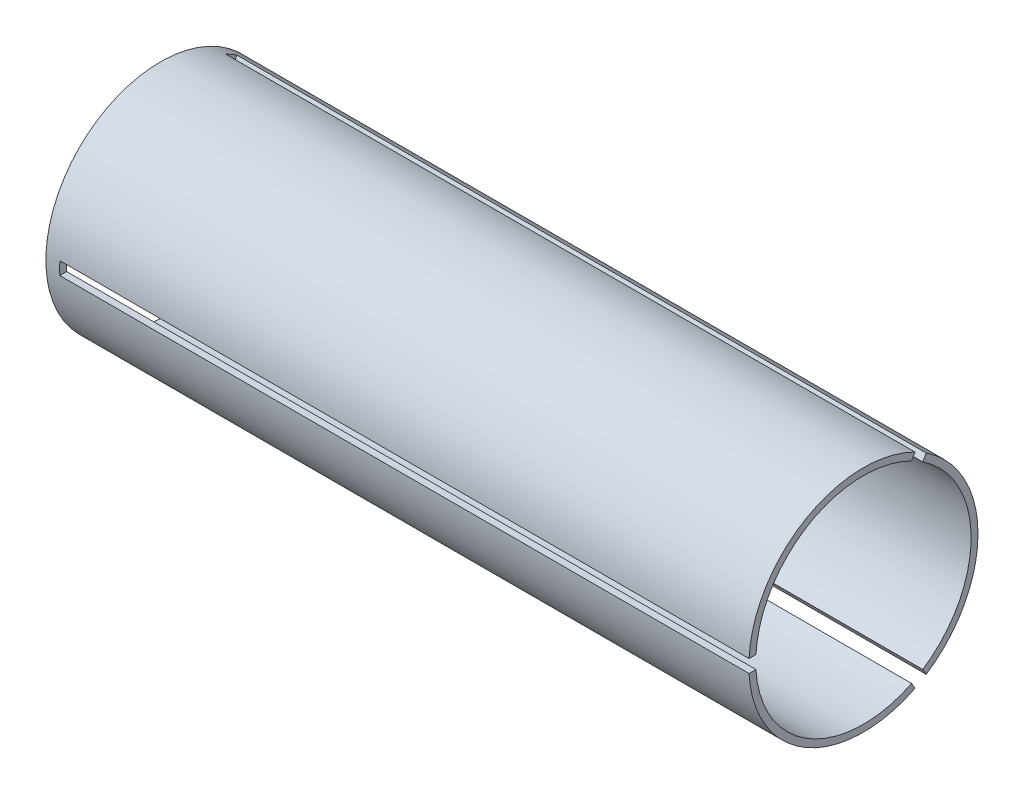
SolidWorks part; units mm, degrees
ref_plane "Front Plane" through (0, 0, 0) normal (1, 0, 0) x (0, 1, 0)
ref_plane "Top Plane" through (0, 0, 0) normal (0, 0, 1) x (0, 1, 0)
ref_plane "Right Plane" through (0, 0, 0) normal (0, 1, 0) x (-1, 0, 0)
sketch "Sketch1" plane through (0, 0, 0) normal (1, 0, 0) x (0, 1, 0)
  circle A0 centre (0, 0) radius 39.6875
  circle A1 centre (0, 0) radius 42.2275
  dimension "D1" = 79.375
  dimension "D2" = 2.54
extrude "Boss-Extrude1" add sketch "Sketch1" along normal blind 259.08
sketch "Sketch2" plane through (0, 0, 0) normal (0, 0, 1) x (0, 1, 0)
  line L0 (-42.2275, -259.08) -> (42.2275, -259.08) construction
  line L1 (-2.3813, -5.08) -> (2.3812, -5.08)
  line L2 (-2.3813, -5.08) -> (-2.3813, -259.08)
  line L3 (-2.3813, -259.08) -> (2.3812, -259.08)
  line L4 (2.3812, -5.08) -> (2.3812, -259.08)
  line L5 (-2.3813, -5.08) -> (2.3812, -259.08) construction
  line L6 (-2.3813, -259.08) -> (2.3812, -5.08) construction
  point P0 (0, -132.08)
  dimension "D1" = 4.7625
  dimension "D2" = 254
extrude "Cut-Extrude1" cut sketch "Sketch2" along normal through all
pattern_circular "CirPattern1" count 3 over 360 about axis through (0, 0, 0) along (1, 0, 0) of "Cut-Extrude1"
